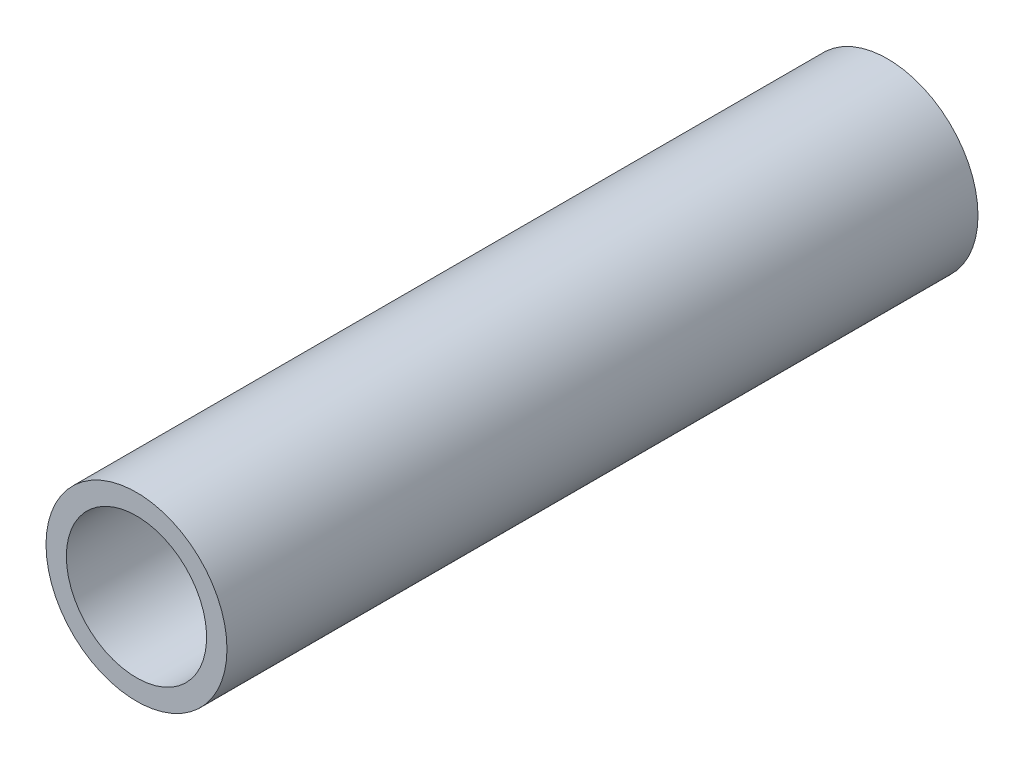
SolidWorks part; units mm, degrees
ref_plane "Спереди" through (0, 0, 0) normal (0, 0, 1) x (1, 0, 0)
ref_plane "Сверху" through (0, 0, 0) normal (0, 1, 0) x (1, 0, 0)
ref_plane "Справа" through (0, 0, 0) normal (1, 0, 0) x (0, 0, -1)
sketch "Эскиз1" plane through (0, 0, 0) normal (0, 0, 1) x (1, 0, 0)
  circle A0 centre (0, 0) radius 1
  circle A1 centre (0, 0) radius 0.775
extrude "Бобышка-Вытянуть1" add sketch "Эскиз1" along normal blind 8.3
